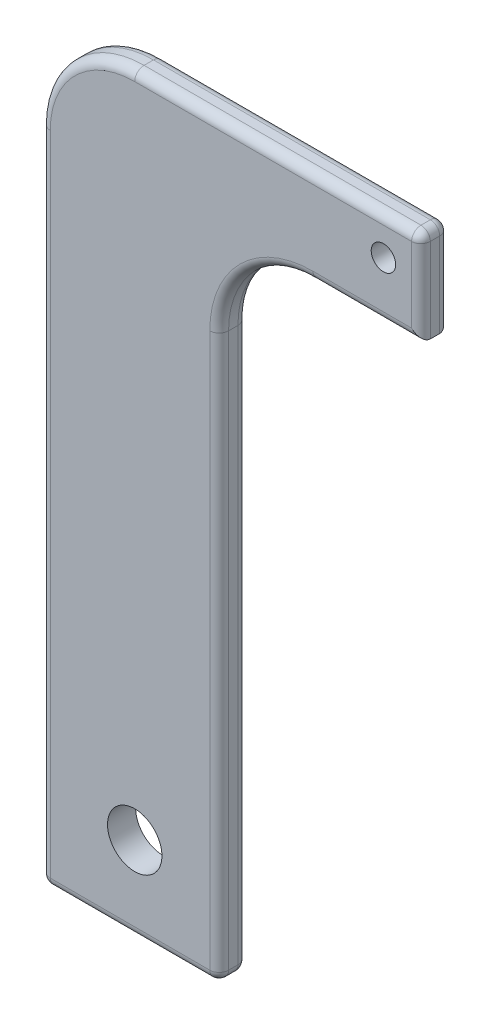
SolidWorks part; units mm, degrees
ref_plane "Plan de face" through (0, 0, 0) normal (0, 0, 1) x (1, 0, 0)
ref_plane "Plan de dessus" through (0, 0, 0) normal (0, 1, 0) x (1, 0, 0)
ref_plane "Plan de droite" through (0, 0, 0) normal (1, 0, 0) x (0, 0, -1)
sketch "Esquisse1" plane through (0, 0, 23) normal (0, 0, 1) x (1, 0, 0)
  line L0 (19, 77) -> (0, 77)
  line L1 (19, 77) -> (19, 157)
  line L2 (0, 77) -> (0, 157)
  line L3 (19, 157) -> (0, 157)
  line L4 (0, 147) -> (0, 157)
  line L5 (0, 147) -> (40.5, 147)
  line L6 (0, 157) -> (40.5, 157)
  line L7 (40.5, 147) -> (40.5, 157)
  line L8 (40.5, 150) -> (40.5, 156) construction
  line L9 (9, 157) -> (0, 157) construction
  line L10 (0, 147) -> (10, 147) construction
  circle A0 centre (10, 86) radius 2.9
  circle A1 centre (36.5, 153) radius 1.3
  circle A2 centre (36.5, 153) radius 1.3 construction
  circle A3 centre (10, 86) radius 2.9 construction
  circle M9 centre (10, 86) radius 2.9
  line M10 (0, 106) -> (0, 77)
  line M11 (0, 77) -> (19, 77)
  line M12 (19, 77) -> (19, 95)
  line M13 (19, 95) -> (10, 95)
  line M14 (10, 95) -> (10, 106)
  line M15 (10, 106) -> (0, 106)
  dimension "D1" = 0
  dimension "D2" = 0
extrude "Boss.-Extru.1" add sketch "Esquisse1" along normal blind 3 contours L5 L2 L1 M15 M14 M13 | M15 M10 M11 M12 M13 M14 M9 | L2 L5 L1 L3 | L5 L7 L6 L1
fillet "Congé1" radius 10 2 edges at (19, 147, 24.5) (0, 157, 24.5)
fillet "Congé2" radius 1 19 edges at (0, 112, 26) (0, 112, 23) (25.25, 157, 23) (25.25, 157, 26) (34.75, 147, 26) (34.75, 147, 23) (19, 107, 23) (19, 107, 26) (0, 77, 24.5) (40.5, 157, 24.5) (2.9289, 154.0711, 26) (2.9289, 154.0711, 23) (40.5, 152, 23) (40.5, 152, 26) (9.5, 77, 23) (9.5, 77, 26) (21.9289, 144.0711, 26) (21.9289, 144.0711, 23) (19, 77, 24.5)
